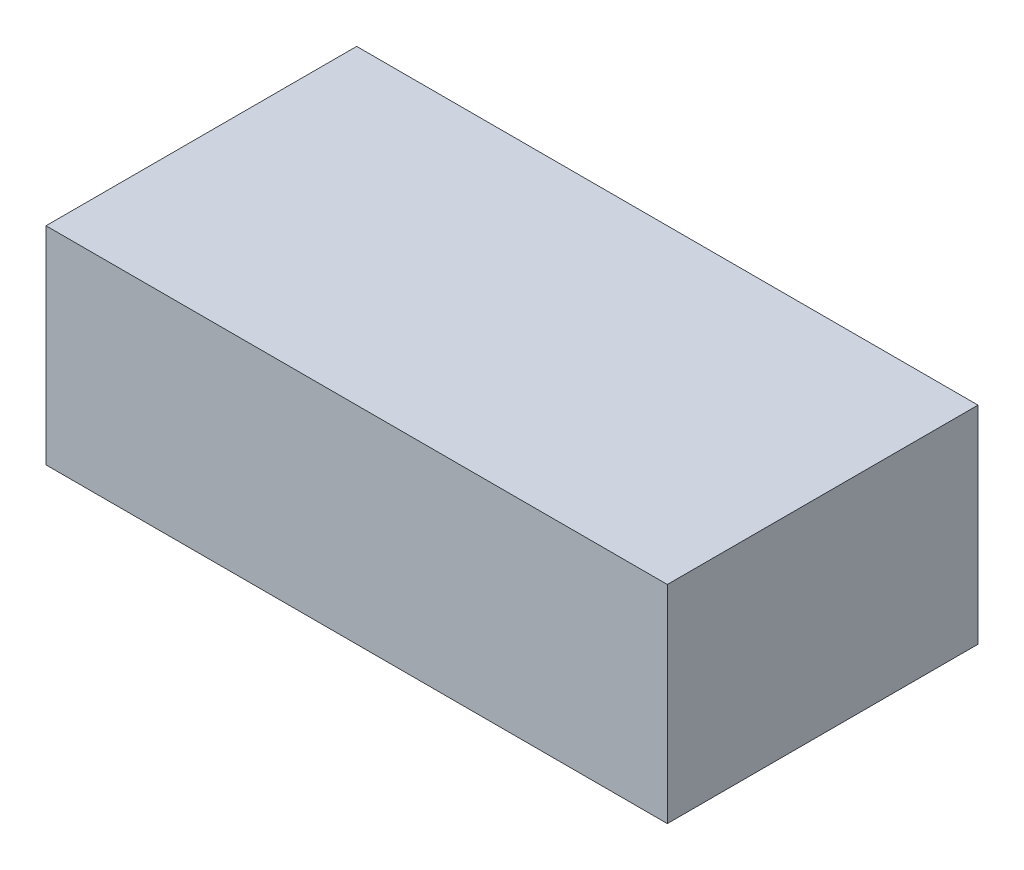
SolidWorks part; units mm, degrees
ref_plane "Front Plane" through (0, 0, 0) normal (0, 0, 1) x (1, 0, 0)
ref_plane "Top Plane" through (0, 0, 0) normal (0, 1, 0) x (1, 0, 0)
ref_plane "Right Plane" through (0, 0, 0) normal (1, 0, 0) x (0, 0, -1)
sketch "Sketch2" plane through (0, 0, 0) normal (0, 1, 0) x (1, 0, 0)
  line L1 (-30, 15) -> (30, 15)
  line L2 (-30, 15) -> (-30, -15)
  line L3 (-30, -15) -> (30, -15)
  line L4 (30, 15) -> (30, -15)
  line L5 (-30, 15) -> (30, -15) construction
  line L6 (-30, -15) -> (30, 15) construction
  point P0 (0, 0)
  dimension "D1" = 30
  dimension "D2" = 60
extrude "Boss-Extrude1" add sketch "Sketch2" along normal blind 20
